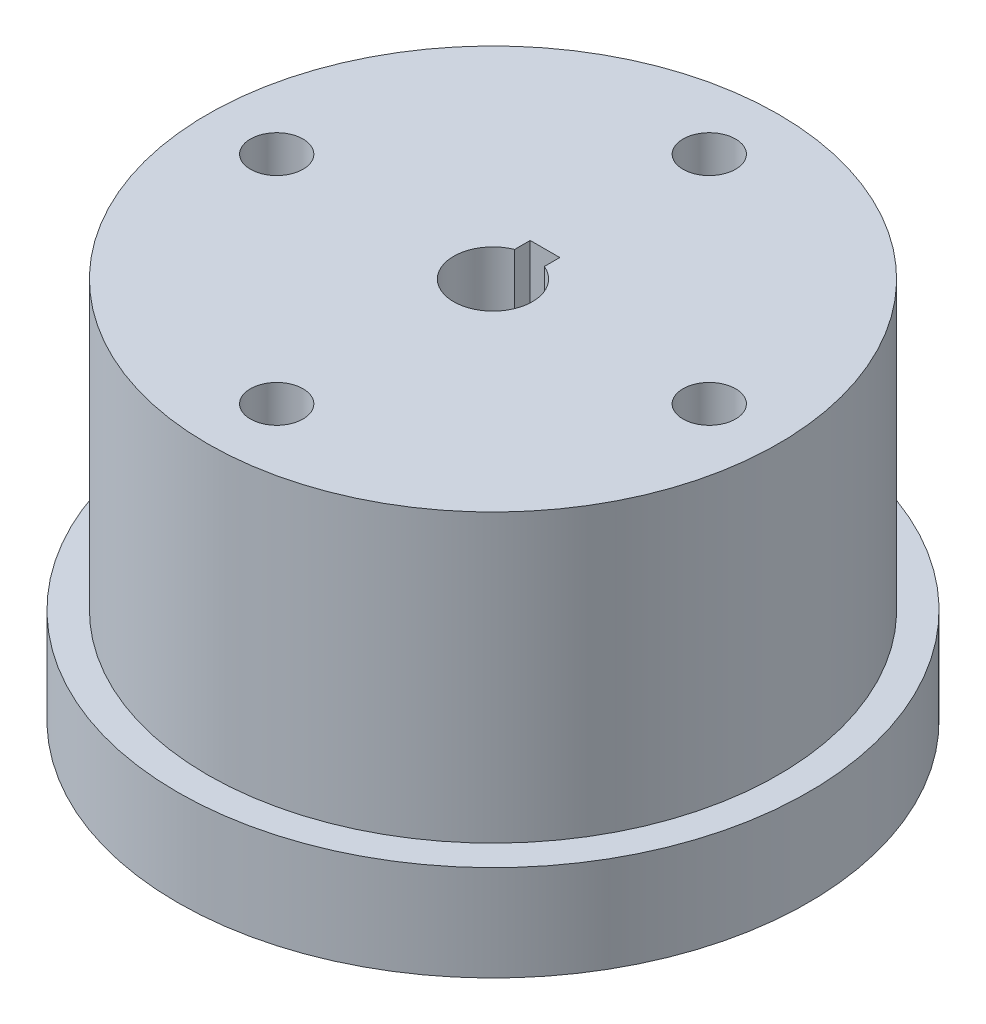
SolidWorks part; units mm, degrees
ref_plane "Front Plane" through (0, 0, 0) normal (0, 0, 1) x (1, 0, 0)
ref_plane "Top Plane" through (0, 0, 0) normal (0, 1, 0) x (1, 0, 0)
ref_plane "Right Plane" through (0, 0, 0) normal (1, 0, 0) x (0, 0, -1)
sketch "Sketch1" plane through (0, 0, 0) normal (0, 1, 0) x (1, 0, 0)
  circle A0 centre (0, 0) radius 33
extrude "Boss-Extrude1" add sketch "Sketch1" along normal blind 10
sketch "Sketch2" plane through (0, 10, 0) normal (0, 1, 0) x (1, 0, 0)
  circle A0 centre (0, 0) radius 29.86
extrude "Boss-Extrude2" add sketch "Sketch2" along normal blind 30
sketch "Sketch3" plane through (0, 40, 0) normal (0, 1, 0) x (1, 0, 0)
  line L1 (0, 22.6274) -> (-22.6274, 0)
  line L2 (-22.6274, 0) -> (0, -22.6274)
  line L3 (0, -22.6274) -> (22.6274, 0)
  line L4 (22.6274, 0) -> (0, 22.6274)
  circle A0 centre (0, 0) radius 16 construction
  circle A1 centre (0, 22.6274) radius 2.75
  circle A2 centre (22.6274, 0) radius 2.75
  circle A3 centre (0, -22.6274) radius 2.75
  circle A4 centre (-22.6274, 0) radius 2.75
  dimension "D1" = 32
extrude "Cut-Extrude1" cut sketch "Sketch3" against normal blind 54 contours L4 A1 L1 | L1 A1 L4 | L3 A2 L4 | L4 A2 L3 | L2 A3 L3 | L3 A3 L2 | L1 A4 L2 | L2 A4 L1
sketch "Sketch4" plane through (0, 40, 0) normal (0, 1, 0) x (1, 0, 0)
  line L0 (0, 4.12) -> (0, 5.44)
  line L1 (0, 5.44) -> (1.55, 5.44)
  line L2 (0, 5.44) -> (-1.55, 5.44)
  line L3 (-1.55, 5.44) -> (-1.55, 3.8173)
  line L4 (1.55, 5.44) -> (1.55, 3.8173)
  circle A0 centre (0, 0) radius 4.12
extrude "Cut-Extrude2" cut sketch "Sketch4" against normal blind 54 contours A0 | A0 L4 L1 L0 | A0 L0 L2 L3
